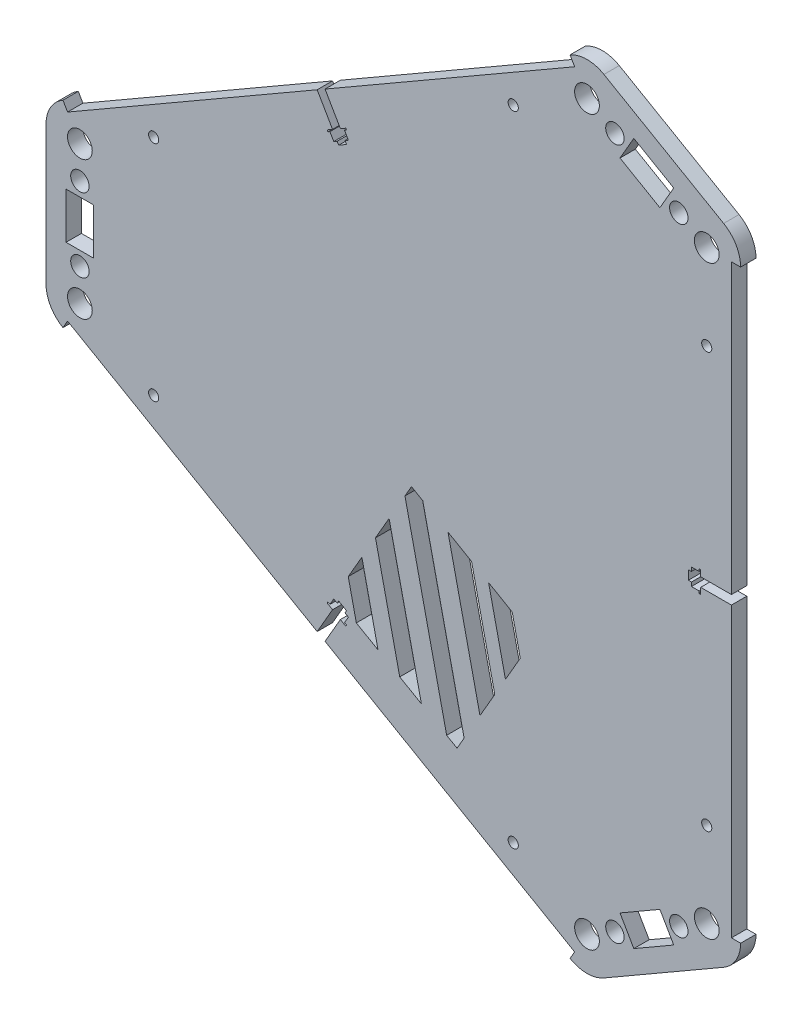
SolidWorks part; units mm, degrees
material "6061-T6 Black anodised"
ref_plane "Front Plane" through (0, 0, 0) normal (0, 0, 1) x (1, 0, 0)
ref_plane "Top Plane" through (0, 0, 0) normal (0, 1, 0) x (1, 0, 0)
ref_plane "Right Plane" through (0, 0, 0) normal (1, 0, 0) x (0, 0, -1)
sketch "Sketch1" plane through (0, 0, 0) normal (0, 0, 1) x (1, 0, 0)
  line L0 (0, 0) -> (-123, 0) construction
  line L1 (-123, 22.5) -> (-123, -22.5) construction
  line L2 (-131.025, 22.4812) -> (-131.025, -22.5) construction
  line L3 (0, 0) -> (61.5, 106.5211) construction
  line L4 (0, 0) -> (61.5, -106.5211) construction
  line L5 (42.0144, 117.7711) -> (80.9856, 95.2711) construction
  line L6 (80.9856, -95.2711) -> (42.0144, -117.7711) construction
  line L7 (46.0269, 124.721) -> (84.9981, 102.221) construction
  line L8 (84.9981, -102.221) -> (46.0269, -124.721) construction
  line L9 (-127.0125, 29.4499) -> (38.0019, 124.721)
  line L10 (89.0106, 95.2711) -> (89.0106, -95.2711)
  line L11 (38.0019, -124.721) -> (-127.0125, -29.4498)
  line L12 (57.2548, -114.1682) -> (70.2452, -106.6682)
  line L13 (57.2548, -114.1682) -> (52.7548, -106.374)
  line L14 (70.2452, -106.6682) -> (65.7452, -98.874)
  line L15 (52.7548, -106.374) -> (65.7452, -98.874)
  line L16 (57.2548, -114.1682) -> (65.7452, -98.874) construction
  line L17 (70.2452, -106.6682) -> (52.7548, -106.374) construction
  line L18 (-118.5, 7.5) -> (-118.5, -7.5)
  line L19 (-127.5, -7.5) -> (-118.5, -7.5)
  line L20 (-127.5, 7.5) -> (-127.5, -7.5)
  line L21 (-127.5, 7.5) -> (-118.5, 7.5)
  line L22 (65.7452, 98.874) -> (52.7548, 106.374)
  line L23 (57.2548, 114.1682) -> (52.7548, 106.374)
  line L24 (70.2452, 106.6682) -> (57.2548, 114.1682)
  line L25 (70.2452, 106.6682) -> (65.7452, 98.874)
  line L26 (-123, 22.5) -> (-99, 36.3564) construction
  line L27 (-99, 36.3564) -> (-99, -36.3564) construction
  line L28 (-99, -36.3564) -> (-123, -22.5) construction
  line L29 (-134.025, 22.5) -> (-134.025, -22.5)
  line L30 (-127.0125, 29.4499) -> (-128.5125, 32.0479)
  line L31 (-127.0125, -29.4498) -> (-128.5125, -32.0479)
  line L32 (38.0019, 124.721) -> (36.5019, 127.3191)
  line L33 (89.0106, 95.2711) -> (92.0106, 95.2711)
  line L34 (47.5269, 127.3191) -> (86.4981, 104.8191)
  line L35 (38.0019, -124.721) -> (36.5019, -127.3191)
  line L36 (89.0106, -95.2711) -> (92.0106, -95.2711)
  line L37 (47.5269, -127.3191) -> (86.4981, -104.8191)
  circle A0 centre (-123, 22.5) radius 4.025
  circle A1 centre (-123, -22.5) radius 4.025
  arc A2 (-127.0125, 29.4499) -> (-131.025, 22.4812) centre (-123, 22.5) ccw construction
  arc A3 (-131.025, -22.5) -> (-127.0125, -29.4498) centre (-123, -22.5) ccw construction
  circle A4 centre (42.0144, 117.7711) radius 4.025
  circle A5 centre (80.9856, 95.2711) radius 4.025
  circle A6 centre (80.9856, -95.2711) radius 4.025
  circle A7 centre (42.0144, -117.7711) radius 4.025
  arc A8 (38.0019, -124.721) -> (46.0269, -124.721) centre (42.0144, -117.7711) ccw construction
  arc A9 (84.9981, -102.221) -> (89.0106, -95.2711) centre (80.9856, -95.2711) ccw construction
  arc A10 (89.0106, 95.2711) -> (84.9981, 102.221) centre (80.9856, 95.2711) ccw construction
  arc A11 (46.0269, 124.721) -> (38.0019, 124.721) centre (42.0144, 117.7711) ccw construction
  circle A12 centre (-99, 36.3564) radius 1.65
  circle A13 centre (-99, -36.3564) radius 1.65
  circle A14 centre (80.9856, 67.5583) radius 1.65
  circle A15 centre (18.0144, 103.9147) radius 1.65
  circle A16 centre (18.0144, -103.9147) radius 1.65
  circle A17 centre (80.9856, -67.5583) radius 1.65
  circle A18 centre (0, 0) radius 65 construction
  arc A19 (-134.025, 22.5) -> (-128.5125, 32.0479) centre (-123, 22.5) cw
  arc A20 (-134.025, -22.5) -> (-128.5125, -32.0479) centre (-123, -22.5) ccw
  arc A21 (47.5269, 127.3191) -> (36.5019, 127.3191) centre (42.0144, 117.7711) ccw
  arc A22 (92.0106, 95.2711) -> (86.4981, 104.8191) centre (80.9856, 95.2711) ccw
  arc A23 (36.5019, -127.3191) -> (47.5269, -127.3191) centre (42.0144, -117.7711) ccw
  arc A24 (86.4981, -104.8191) -> (92.0106, -95.2711) centre (80.9856, -95.2711) ccw
  circle A25 centre (-123, 12) radius 3
  circle A26 centre (-123, -12) radius 3
  circle A27 centre (71.8923, 100.5211) radius 3
  circle A28 centre (51.1077, 112.5211) radius 3
  circle A29 centre (51.1077, -112.5211) radius 3
  circle A30 centre (71.8923, -100.5211) radius 3
  point P44 (0, 0)
  point P56 (0, 0)
  point P79 (0, 0)
  point P84 (0, 0)
  dimension "D3" = 8.05
  dimension "D9" = 3.3
  dimension "D12" = 130
  dimension "D15" = 6
  dimension "D1" = 123
  dimension "D2" = 45
  dimension "D4" = 120
  dimension "D5" = 4
  dimension "D6" = 9
  dimension "D7" = 15
  dimension "D10" = 24
  dimension "D13" = 3
  dimension "D14" = 12
  dimension "D16" = 12
  dimension "D8" = 3
  dimension "D11" = 3
  dimension "D17" = 3
extrude "Boss-Extrude1" add sketch "Sketch1" along normal blind 5
sketch "Sketch2" plane through (0, 0, 5) normal (0, 0, 1) x (1, 0, 0)
  line L0 (0, 0) -> (89.0106, 0) construction
  line L1 (89.0106, -95.2711) -> (89.0106, 95.2711) construction
  line L2 (89.0106, 1.48) -> (79.0106, 1.48)
  line L3 (79.0106, 1.48) -> (79.0106, 3.5)
  line L4 (79.0106, 3.5) -> (78.5106, 3.5)
  line L5 (78.5106, 3.5) -> (78.5106, 2.75)
  line L6 (78.5106, 2.75) -> (76.0106, 2.75)
  line L7 (76.0106, 2.75) -> (76.0106, 1.48)
  line L8 (76.0106, 1.48) -> (75.0106, 1.48)
  line L9 (75.0106, 1.48) -> (75.0106, -1.48)
  line L10 (89.0106, -1.48) -> (89.0106, 1.48)
  line L11 (76.0106, -1.48) -> (75.0106, -1.48)
  line L12 (76.0106, -2.75) -> (76.0106, -1.48)
  line L13 (78.5106, -2.75) -> (76.0106, -2.75)
  line L14 (78.5106, -3.5) -> (78.5106, -2.75)
  line L15 (79.0106, -3.5) -> (78.5106, -3.5)
  line L16 (79.0106, -1.48) -> (79.0106, -3.5)
  line L17 (89.0106, -1.48) -> (79.0106, -1.48)
  line L18 (-43.2236, -77.8254) -> (-38.2236, -69.1652)
  line L19 (-38.2236, -69.1652) -> (-36.4742, -70.1752)
  line L20 (-36.4742, -70.1752) -> (-36.2242, -69.7421)
  line L21 (-36.2242, -69.7421) -> (-36.8737, -69.3671)
  line L22 (-36.8737, -69.3671) -> (-35.6237, -67.2021)
  line L23 (-35.6237, -67.2021) -> (-36.7236, -66.5671)
  line L24 (-36.7236, -66.5671) -> (-36.2236, -65.7011)
  line L25 (-36.2236, -65.7011) -> (-38.787, -64.2211)
  line L26 (-39.287, -65.0871) -> (-38.787, -64.2211)
  line L27 (-40.3869, -64.4521) -> (-39.287, -65.0871)
  line L28 (-41.6369, -66.6171) -> (-40.3869, -64.4521)
  line L29 (-42.2864, -66.2421) -> (-41.6369, -66.6171)
  line L30 (-42.5364, -66.6752) -> (-42.2864, -66.2421)
  line L31 (-40.787, -67.6852) -> (-42.5364, -66.6752)
  line L32 (-45.787, -76.3454) -> (-40.787, -67.6852)
  line L33 (-45.787, -76.3454) -> (-43.2236, -77.8254)
  line L34 (-45.787, 76.3454) -> (-40.787, 67.6852)
  line L35 (-40.787, 67.6852) -> (-42.5364, 66.6752)
  line L36 (-42.5364, 66.6752) -> (-42.2864, 66.2421)
  line L37 (-42.2864, 66.2421) -> (-41.6369, 66.6171)
  line L38 (-41.6369, 66.6171) -> (-40.3869, 64.4521)
  line L39 (-40.3869, 64.4521) -> (-39.287, 65.0871)
  line L40 (-39.287, 65.0871) -> (-38.787, 64.2211)
  line L41 (-38.787, 64.2211) -> (-36.2236, 65.7011)
  line L42 (-36.7236, 66.5671) -> (-36.2236, 65.7011)
  line L43 (-35.6237, 67.2021) -> (-36.7236, 66.5671)
  line L44 (-36.8737, 69.3671) -> (-35.6237, 67.2021)
  line L45 (-36.2242, 69.7421) -> (-36.8737, 69.3671)
  line L46 (-36.4742, 70.1752) -> (-36.2242, 69.7421)
  line L47 (-38.2236, 69.1652) -> (-36.4742, 70.1752)
  line L48 (-43.2236, 77.8254) -> (-38.2236, 69.1652)
  line L49 (-43.2236, 77.8254) -> (-45.787, 76.3454)
  point P16 (75.0106, 0)
  point P56 (0.0125, 0.0072)
  point P58 (0, 0)
  point P59 (0, 0)
  dimension "D1" = 0.5
  dimension "D2" = 2.5
  dimension "D3" = 14
  dimension "D4" = 2.96
  dimension "D5" = 7
  dimension "D6" = 5.5
  dimension "D7" = 1
  dimension "D8" = 3
extrude "Cut-Extrude1" cut sketch "Sketch2" against normal through all
sketch "Sketch3" plane through (0, 0, 5) normal (0, 0, 1) x (1, 0, 0)
  line L0 (-15.1034, -20.1598) -> (-40.1034, -63.461) construction
  line L1 (-15.1034, -20.1598) -> (24.7338, -43.1598) construction
  line L2 (-40.1034, -63.461) -> (-0.2662, -86.4611) construction
  line L3 (24.7338, -43.1598) -> (-0.2662, -86.4611) construction
  line L4 (-15.1034, -20.1598) -> (-0.2662, -86.4611) construction
  line L5 (-40.1034, -63.461) -> (24.7338, -43.1598) construction
  line L6 (-20.1848, -74.961) -> (-27.1848, -87.0854) construction
  line L7 (-43.2236, -77.8254) -> (38.0019, -124.721) construction
  line L8 (-35.6724, -55.7864) -> (-33.0427, -67.5375)
  line L9 (-33.0427, -67.5375) -> (-25.9821, -71.614)
  line L10 (-25.9821, -71.614) -> (-31.2415, -48.1118)
  line L11 (-31.2415, -48.1118) -> (-35.6724, -55.7864)
  line L12 (-26.8105, -40.4372) -> (-18.9214, -75.6905)
  line L13 (-18.9214, -75.6905) -> (-11.8608, -79.7669)
  line L14 (-11.8608, -79.7669) -> (-22.3796, -32.7626)
  line L15 (-22.3796, -32.7626) -> (-26.8105, -40.4372)
  line L16 (-17.2265, -23.8372) -> (-3.6494, -84.5077)
  line L17 (-3.6494, -84.5077) -> (-0.2662, -86.4611)
  line L18 (-0.2662, -86.4611) -> (2.0416, -82.4639)
  line L19 (2.0416, -82.4639) -> (-11.4259, -22.2829)
  line L20 (-22.3796, -32.7626) -> (-15.5702, -31.2387) construction
  line L21 (-3.2146, -27.0238) -> (7.1946, -73.5385)
  line L22 (7.1946, -73.5385) -> (12.0109, -65.1965)
  line L23 (12.0109, -65.1965) -> (4.46, -31.4547)
  line L24 (4.46, -31.4547) -> (-3.2146, -27.0238)
  line L25 (9.9985, -34.6524) -> (15.4866, -59.1764)
  line L26 (15.4866, -59.1764) -> (20.3029, -50.8344)
  line L27 (20.3029, -50.8344) -> (17.6732, -39.0833)
  line L28 (17.6732, -39.0833) -> (9.9985, -34.6524)
  line L29 (-11.4259, -22.2829) -> (-15.1034, -20.1598)
  line L30 (-15.1034, -20.1598) -> (-17.2265, -23.8372)
  line L31 (-3.2146, -27.0238) -> (-10.024, -28.5476) construction
  point P1 (-7.6848, -53.3104)
  dimension "D1" = 20
  dimension "D2" = 46
  dimension "D3" = 50
  dimension "D4" = 14
  dimension "D5" = 6
  dimension "D6" = 6
  dimension "D7" = 6
  dimension "D8" = 6
  dimension "D9" = 6
extrude "Cut-Extrude2" cut sketch "Sketch3" against normal through all
equation "\"D16@Sketch1\"=\"D14@Sketch1\""
